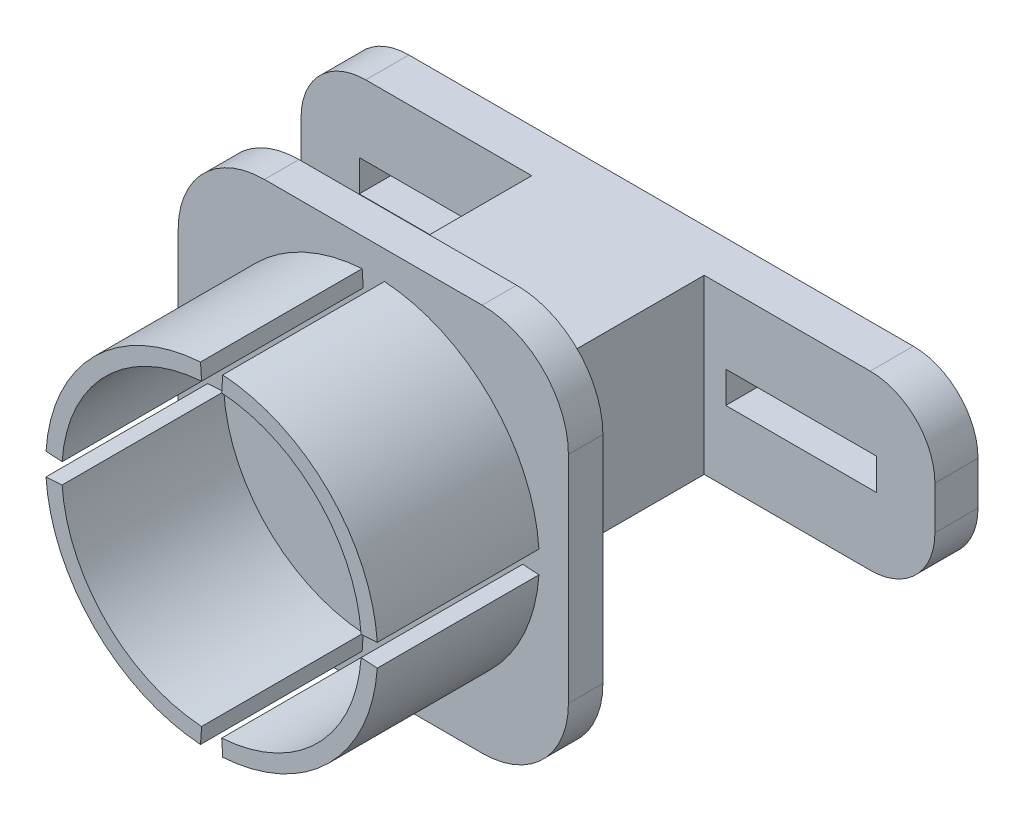
SolidWorks part; units mm, degrees
ref_plane "Front Plane" through (0, 0, 0) normal (0, 0, 1) x (1, 0, 0)
ref_plane "Top Plane" through (0, 0, 0) normal (0, 1, 0) x (1, 0, 0)
ref_plane "Right Plane" through (0, 0, 0) normal (1, 0, 0) x (0, 0, -1)
sketch "Sketch1" plane through (0, 0, 0) normal (0, 0, 1) x (1, 0, 0)
  line L0 (-12, 0.73) -> (-5, 0.73)
  line L1 (-11.7, 4) -> (11.7, 4)
  line L2 (-14.7, 1) -> (-14.7, -1)
  line L3 (-11.7, -4) -> (11.7, -4)
  line L4 (14.7, 1) -> (14.7, -1)
  line L5 (5, 0.73) -> (12, 0.73)
  line L6 (5, 0.73) -> (5, -0.73)
  line L7 (5, -0.73) -> (12, -0.73)
  line L8 (12, 0.73) -> (12, -0.73)
  line L9 (-12, 0.73) -> (-12, -0.73)
  line L10 (-12, -0.73) -> (-5, -0.73)
  line L11 (-5, 0.73) -> (-5, -0.73)
  arc A0 (11.7, 4) -> (14.7, 1) centre (11.7, 1) cw
  arc A1 (11.7, -4) -> (14.7, -1) centre (11.7, -1) ccw
  arc A2 (-14.7, -1) -> (-11.7, -4) centre (-11.7, -1) ccw
  arc A3 (-11.7, 4) -> (-14.7, 1) centre (-11.7, 1) ccw
  point P12 (-14.7, 0)
  dimension "D7" = 3
  dimension "D1" = 7
  dimension "D2" = 1.46
  dimension "D3" = 2.7
  dimension "D4" = 2.7
  dimension "D5" = 3.27
  dimension "D6" = 3.27
extrude "Boss-Extrude1" add sketch "Sketch1" along normal blind 2
sketch "Sketch2" plane through (0, 0, 0) normal (0, 0, 1) x (1, 0, 0)
  line L0 (11.7, 4) -> (-11.7, 4) construction
  line L1 (-4, 4) -> (4, 4)
  line L2 (-4, 4) -> (-4, -4)
  line L3 (-4, -4) -> (4, -4)
  line L4 (4, 4) -> (4, -4)
  line L5 (-11.7, -4) -> (11.7, -4) construction
  dimension "D1" = 8
  dimension "D2" = 4
extrude "Boss-Extrude2" add sketch "Sketch2" along normal blind 11.7499
sketch "Sketch3" plane through (0, 0, 11.7499) normal (0, 0, 1) x (1, 0, 0)
  line L1 (-5.05, 9.0001) -> (5.05, 9.0001)
  line L2 (-9.05, 5.0001) -> (-9.05, -5.0001)
  line L3 (-5.05, -9.0001) -> (5.05, -9.0001)
  line L4 (9.05, 5.0001) -> (9.05, -5.0001)
  line L5 (-9.05, 9.0001) -> (9.05, -9.0001) construction
  line L6 (-9.05, -9.0001) -> (9.05, 9.0001) construction
  arc A0 (-9.05, -5.0001) -> (-5.05, -9.0001) centre (-5.05, -5.0001) ccw
  arc A1 (5.05, -9.0001) -> (9.05, -5.0001) centre (5.05, -5.0001) ccw
  arc A2 (5.05, 9.0001) -> (9.05, 5.0001) centre (5.05, 5.0001) cw
  arc A3 (-5.05, 9.0001) -> (-9.05, 5.0001) centre (-5.05, 5.0001) ccw
  point P0 (0, 0)
  dimension "D2" = 4
  dimension "D1" = 9.05
extrude "Boss-Extrude3" add sketch "Sketch3" along normal blind 1.6
sketch "Sketch4" plane through (0, 0, 13.3499) normal (0, 0, 1) x (1, 0, 0)
  circle A1 centre (0, 0) radius 7.7
  dimension "D2" = 15.4
extrude "Boss-Extrude4" add sketch "Sketch4" along normal blind 7.5
sketch "Sketch5" plane through (0, 0, 13.3499) normal (0, 0, 1) x (1, 0, 0)
  circle A0 centre (0, 0) radius 6.95
  dimension "D1" = 13.9
extrude "Cut-Extrude1" cut sketch "Sketch5" along normal blind 7.5
sketch "Sketch11" plane through (0, 0, 13.3499) normal (0, 0, 1) x (1, 0, 0)
  line L4 (0, 8.1838) -> (-0.55, 8.1838)
  line L5 (-0.55, 8.1838) -> (0, 0)
  line L6 (0, 8.1838) -> (0.55, 8.1838)
  line L7 (0.55, 8.1838) -> (0, 0)
  dimension "D1" = 0.55
  dimension "D2" = 0.55
extrude "Cut-Extrude2" cut sketch "Sketch11" along normal blind 7.5
pattern_circular "CirPattern1" count 4 every 90 about axis through (0, 0, 20.8499) along (0, 0, -1) of "Cut-Extrude2"
